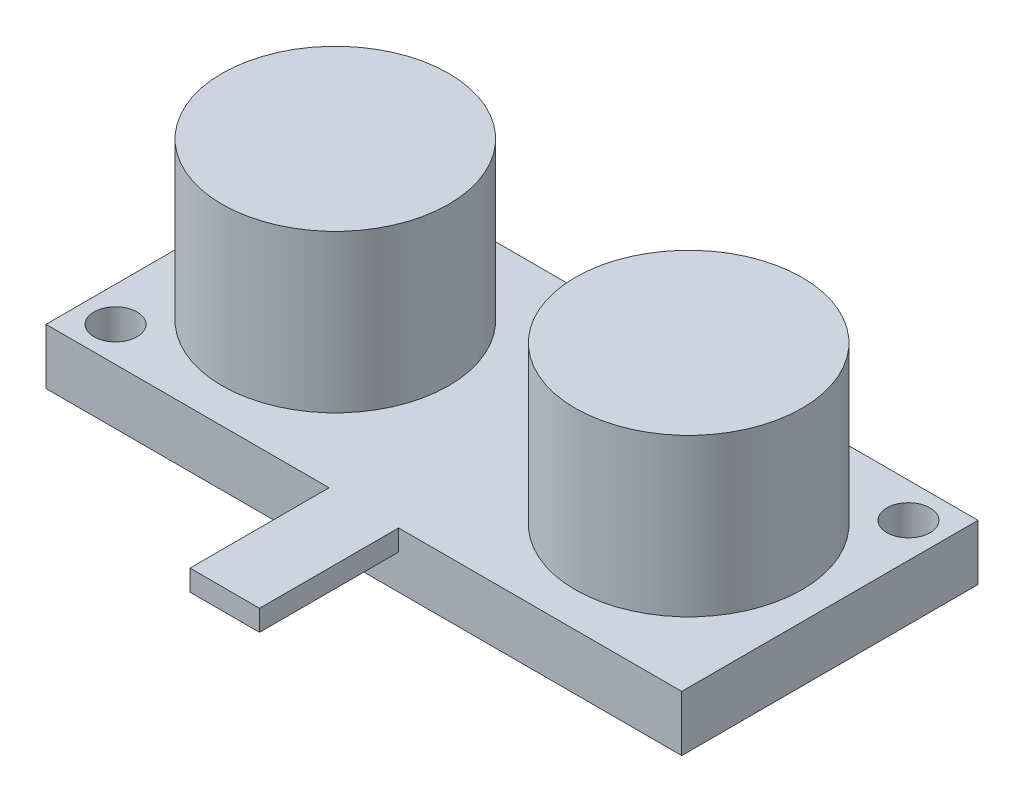
SolidWorks part; units mm, degrees
ref_plane "Front Plane" through (0, 0, 0) normal (0, 0, 1) x (1, 0, 0)
ref_plane "Top Plane" through (0, 0, 0) normal (0, 1, 0) x (1, 0, 0)
ref_plane "Right Plane" through (0, 0, 0) normal (1, 0, 0) x (0, 0, -1)
ref_plane "Plane1" through (0, 0, 0) normal (0, 1, 0) x (1, 0, 0)
sketch "Sketch1" plane through (0, 0, 0) normal (0, 1, 0) x (1, 0, 0)
  line L0 (0, 0) -> (45.7, 0)
  line L1 (45.7, 0) -> (45.7, 21.3)
  line L2 (45.7, 21.3) -> (0, 21.3)
  line L3 (0, 21.3) -> (0, 0)
  circle A0 centre (43.2, 18.8) radius 1.55
  circle A1 centre (2.5, 2.5) radius 1.55
  dimension "D1" = 3.1
  dimension "D2" = 21.3
  dimension "D3" = 45.7
  dimension "D4" = 45.7
extrude "Boss-Extrude1" add sketch "Sketch1" along normal blind 4
sketch "Sketch2" plane through (0, 4, 0) normal (0, 1, 0) x (-1, 0, 0)
  circle A0 centre (-35.55, -10.65) radius 8.15
  circle A1 centre (-10.15, -10.65) radius 8.15
extrude "Boss-Extrude2" add sketch "Sketch2" along normal blind 11.3
sketch "Sketch3" plane through (0, 0, 0) normal (0, 0, 1) x (1, 0, 0)
  line L0 (20.35, 4) -> (25.35, 4)
  line L1 (25.35, 4) -> (25.35, 2.5)
  line L2 (25.35, 2.5) -> (20.35, 2.5)
  line L3 (20.35, 2.5) -> (20.35, 4)
extrude "Boss-Extrude3" add sketch "Sketch3" along normal blind 10
